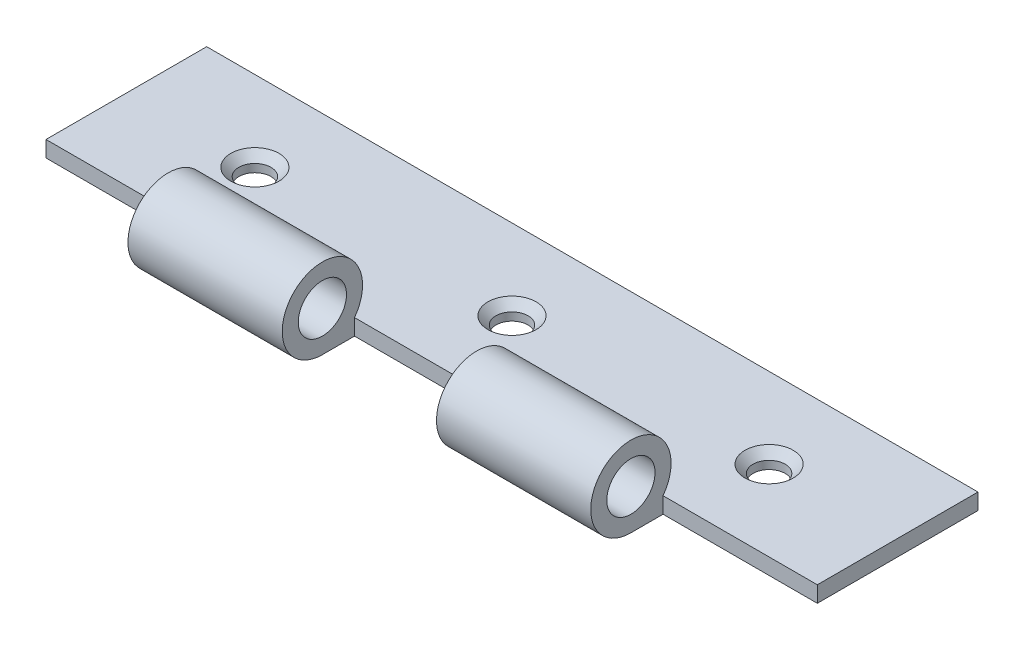
SolidWorks part; units mm, degrees
ref_plane "Front Plane" through (0, 0, 0) normal (0, 0, 1) x (1, 0, 0)
ref_plane "Top Plane" through (0, 0, 0) normal (0, 1, 0) x (1, 0, 0)
ref_plane "Right Plane" through (0, 0, 0) normal (1, 0, 0) x (0, 0, -1)
sketch "Sketch1" plane through (0, 0, 0) normal (0, 1, 0) x (1, 0, 0)
  line L1 (-38.1, -9.525) -> (38.1, -9.525)
  line L2 (-38.1, -9.525) -> (-38.1, 9.525)
  line L3 (-38.1, 9.525) -> (38.1, 9.525)
  line L4 (38.1, -9.525) -> (38.1, 9.525)
  line L5 (-38.1, -9.525) -> (38.1, 9.525) construction
  line L6 (-38.1, 9.525) -> (38.1, -9.525) construction
  point P0 (0, 0)
  dimension "D1" = 76.2
  dimension "D2" = 19.05
extrude "Boss-Extrude1" add sketch "Sketch1" along normal blind 1.5875
sketch "Sketch2" plane through (38.1, 0, 0) normal (1, 0, 0) x (0, 0, -1)
  circle A0 centre (-9.525, 3.9688) radius 3.9688
  circle A1 centre (-9.525, 3.9688) radius 2.3813
  dimension "D1" = 7.9375
  dimension "D2" = 4.7625
extrude "Boss-Extrude2" add sketch "Sketch2" against normal up to surface (76.2 mm away) up to face at (-38.1, 0.7937, 0)
ref_plane "Tangent Plane" through (0, 0, 5.5562) normal (0, 0, -1) x (-1, 0, 0)
sketch "Sketch4" plane through (0, 1.5875, 0) normal (0, 1, 0) x (1, 0, 0)
  line L0 (38.1, 1.5875) -> (-49961.9, 1.5875) construction
  line L2 (38.1, -6.35) -> (38.1, 9.525) construction
  line L3 (-38.1, 9.525) -> (-38.1, -6.35) construction
  circle A0 centre (-25.4, 1.5875) radius 1.5875
  point P4 (38.1, 1.5875)
  dimension "D1" = 12.7
extrude "Cut-Extrude1" cut sketch "Sketch4" against normal through all
chamfer "Chamfer1" distance 0.7937 1 edges at (-25.4, 1.5875, 0)
pattern_linear "LPattern1" count 3 spacing 25.4 along (1, 0, 0) of "Chamfer1", "Cut-Extrude1"
sketch "Sketch5" plane through (38.1, 0, 0) normal (1, 0, 0) x (0, 0, -1)
  line L0 (-6.35, 1.5875) -> (-6.35, 0)
  line L3 (9.525, 1.5875) -> (-6.35, 1.5875)
  line L4 (-9.525, 0) -> (9.525, 0)
  line L5 (9.525, 0) -> (9.525, 1.5875)
  line L7 (-9.525, 0) -> (-6.35, 0)
  arc A1 (-6.35, 1.5875) -> (-9.525, 0) centre (-9.525, 3.9688) ccw
  arc A2 (-6.35, 1.5875) -> (-9.525, 0) centre (-9.525, 3.9688) ccw
  dimension "D1" = 0
extrude "Cut-Extrude2" cut sketch "Sketch5" against normal blind 15.24
pattern_linear "LPattern2" count 5 spacing 15.24 along (-1, 0, 0) skipping (1, 0), (3, 0) of "Cut-Extrude2"
